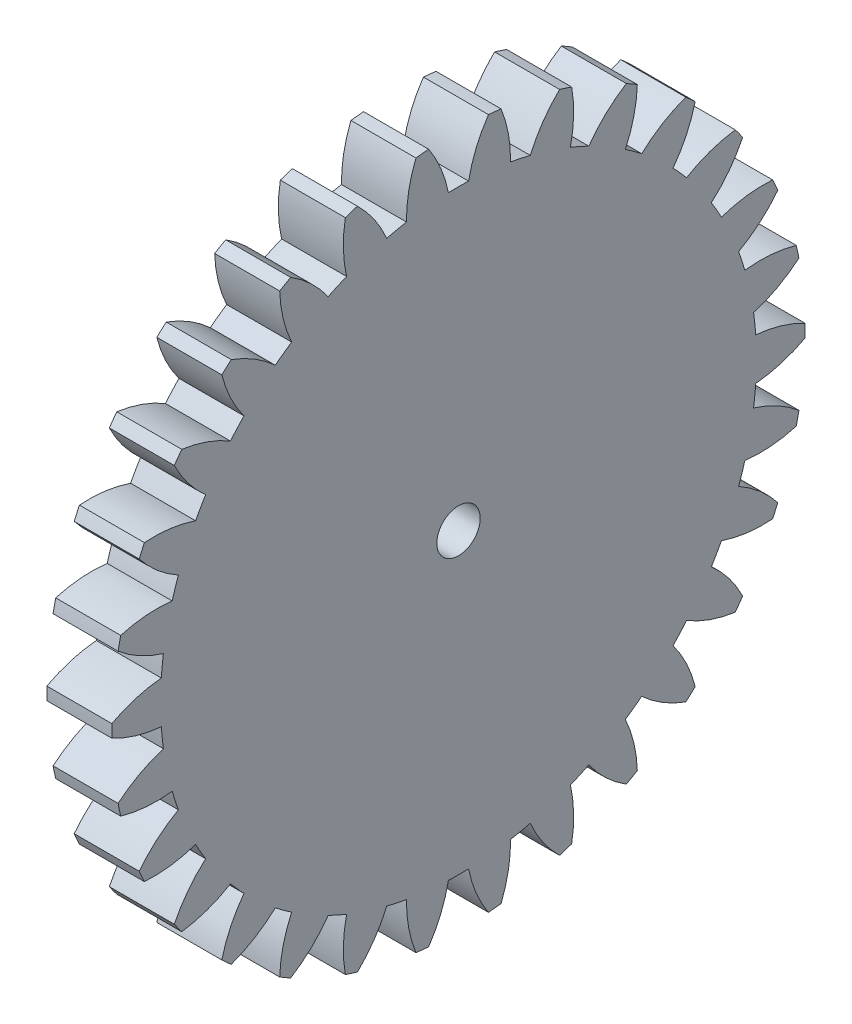
SolidWorks part; units mm, degrees
ref_plane "Plane1" through (0, 0, 0) normal (0, 0, 1) x (1, 0, 0)
ref_plane "Plane2" through (0, 0, 0) normal (0, 1, 0) x (1, 0, 0)
ref_plane "Plane3" through (0, 0, 0) normal (1, 0, 0) x (0, 0, -1)
sketch "HoldingSke" plane through (0, 0, 0) normal (0, 1, 0) x (1, 0, 0)
  line L0 (0, 0) -> (0.866, -0.5)
  line L1 (-15, 0) -> (100, 0) construction
  line L2 (0, 0) -> (-2.1039, 2.3779)
  line L3 (0, 0) -> (-11.863, 4.5341)
  line L4 (0, 0) -> (7.479, 4.318)
  line L5 (0, 0) -> (-46.8476, -17.4728)
  line L6 (0, 0) -> (-2.4869, -1.6779)
  line L7 (-2.1039, 2.3779) -> (8.6586, 51.2059)
  line L8 (-76.2, 54.61) -> (-75.9, 54.61)
  line L9 (-71.009, 38.7566) -> (-53.1078, 45.2721)
  line L10 (-76.2, 71.12) -> (104.1128, 71.12)
  line L11 (0, 0) -> (-3, 0)
  line L12 (-76.2, 101.6) -> (-76.162, 101.6)
  line L13 (24.9733, 27.94) -> (52.9518, 28.4284)
  line L14 (24.9733, 27.94) -> (24.9743, 27.94)
  line L15 (24.9733, 27.94) -> (100.4006, 29.5858)
  line L16 (-63.627, -1) -> (-12.827, -1)
  circle A0 centre (0, 0) radius 1
  circle A1 centre (0, 0) radius 13.749
  circle A2 centre (0, 0) radius 37.5
  circle A3 centre (0, 0) radius 1
  dimension "MHD" = 27.498
  dimension "Hub_dia" = 75
  dimension "Bore" = 2
  dimension "MBD" = 2
  dimension "Num_teeth" = 30
  dimension "Pitch" = 1
  dimension "Overall_len" = 50
  dimension "Show_teeth" = 30
  dimension "Thickness" = 3
  dimension "OAL" = 50.0001
  dimension "T_dim" = 0.3
  dimension "Ap" = 20
  dimension "H" = 19.05
  dimension "Pitch_radius" = 180.3128
  dimension "Width" = 3
  dimension "Backlash" = 0.038
  dimension "Addendum_fac" = 1
  dimension "Dedendum_fac" = 1.25
  dimension "Clearance_fac" = 0.25
  dimension "Dedendum_add" = 0.001
  dimension "Module" = 1
sketch "BasProSke" plane through (0, 0, 0) normal (0, 1, 0) x (1, 0, 0)
  line L0 (-10, 0) -> (60, 0) construction
  line L1 (0, 0) -> (0, 16)
  line L2 (0, 0) -> (3, 0)
  line L3 (3, 0) -> (3, 16)
  line L4 (3, 16) -> (0, 16)
  dimension "Thickness" = 3
  dimension "Diameter" = 32
revolve "Base-Revolve" add sketch "BasProSke" angle 360 about L0
sketch "TooCutSke" plane through (0, 0, 0) normal (1, 0, 0) x (0, 0, -1)
  line L1 (0, 0) -> (0, 107) construction
  line L2 (0, 0) -> (-0.8515, 14.9758) construction
  line L3 (0, 0) -> (-3.1323, 29.8014) construction
  line L4 (-0.8515, 14.9758) -> (-1.5661, 14.9007) construction
  arc A0 (0.4664, 13.7411) -> (-0.4664, 13.7411) centre (0, 0) ccw
  arc A1 (1.3975, 15.9644) -> (-1.3975, 15.9644) centre (0, 0) ccw
  circle A2 centre (0, 0) radius 15 construction
  circle A3 centre (0, 0) radius 14.0954 construction
  arc A4 (-0.4664, 13.7411) -> (-1.3975, 15.9644) centre (-6.3534, 12.5823) ccw
  arc A5 (1.3975, 15.9644) -> (0.4664, 13.7411) centre (6.3534, 12.5823) ccw
  dimension "Root_dia" = 27.498
  dimension "Overcut_dia" = 32.0508
  dimension "Pitch_dia" = 30
  dimension "Base_dia" = 28.1908
  dimension "Flank_rad" = 6
  dimension "Half_ang" = 6
  dimension "Half_CT" = 0.7185
extrude "ToothCut" cut sketch "TooCutSke" along normal through all
fillet "Breaks" [suppressed] radius 0.02
fillet "RootFillets" [suppressed] radius 0.251
pattern_circular "TeethCuts" count 30 every 12 about axis through (-10, 0, 0) along (1, 0, 0) of "ToothCut", "RootFillets", "Breaks"
sketch "HubNeaOneSke" plane through (0, 0, 0) normal (-1, 0, 0) x (0, 0, 1)
  circle A0 centre (0, 0) radius 13.749
  dimension "Diameter" = 27.498
extrude "HubNearOne" [suppressed] add sketch "HubNeaOneSke" along normal blind 47.0001
sketch "HubNeaBotSke" plane through (0, 0, 0) normal (-1, 0, 0) x (0, 0, 1)
  circle A0 centre (0, 0) radius 13.749
  dimension "Diameter" = 27.498
extrude "HubNearBoth" [suppressed] add sketch "HubNeaBotSke" along normal blind 23.5
ref_plane "FarPln" through (3, 0, 0) normal (1, 0, 0) x (0, 0, -1)
sketch "HubFarSke" plane through (3, 0, 0) normal (1, 0, 0) x (0, 0, -1)
  circle A0 centre (0, 0) radius 13.749
  dimension "Diameter" = 27.498
extrude "HubFar" [suppressed] add sketch "HubFarSke" along normal blind 23.5
sketch "BorSke" plane through (0, 0, 0) normal (1, 0, 0) x (0, 0, -1)
  circle A0 centre (0, 0) radius 1
  dimension "Diameter" = 2
extrude "Bore" cut sketch "BorSke" along normal mid plane 100.0001
sketch "KeySke" plane through (0, 0, 0) normal (1, 0, 0) x (0, 0, -1)
  line L0 (-0.4, 0) -> (-0.4, 1.3)
  line L1 (-0.4, 1.3) -> (0.4, 1.3)
  line L2 (0.4, 1.3) -> (0.4, 0)
  line L3 (0, 0) -> (0, 34) construction
  line L4 (-0.4, 0) -> (0.4, 0)
  dimension "Offset" = 1.3
  dimension "Width" = 0.8
extrude "Keyway" [suppressed] cut sketch "KeySke" along normal mid plane 100.0001
pattern_circular "Keyway2" [suppressed] count 2 every 90 about axis through (-10, 0, 0) along (1, 0, 0)
equation "' \"Module@HoldingSke\" = 6.35"
equation "' \"Num_teeth@HoldingSke\" = 12"
equation "' \"Ap@HoldingSke\" =  20"
equation "' \"Ap@HoldingSke\" = 20"
equation "' \"Width@HoldingSke\" = 0.5 * 25.4"
equation "' \"Hub_dia@HoldingSke\"= 1 * 25.4"
equation "' \"Hub_dia@HoldingSke\" = 1 * 25.4"
equation "' \"Overall_len@HoldingSke\" = 1.0 * 25.4"
equation "' \"Bore@HoldingSke\" = 0.75 * 25.4"
equation "' \"T_dim@HoldingSke\" = 0.1 * 25.4"
equation "' \"Width@KeySke\" = 0.25 * 25.4"
equation "' \"Show_teeth@HoldingSke\" = 13"
equation "' \"Backlash@HoldingSke\" = 0.009 * 25.4"
equation "' \"Addendum_fac@HoldingSke\" = 1.0"
equation "' \"Dedendum_fac@HoldingSke\" = 1.25"
equation "' \"Dedendum_add@HoldingSke\" = 0.00005 * 25.4"
equation "' \"Clearance_fac@HoldingSke\" = 0.25"
equation "\"Pitch@HoldingSke\" = 1 / \"Module@HoldingSke\""
equation "\"Overcut_dia@TooCutSke\" = (\"Num_teeth@HoldingSke\" + 2 * \"Addendum_fac@HoldingSke\") / \"Pitch@HoldingSke\" + 0.002 * 25.4"
equation "\"Pitch_dia@TooCutSke\" = \"Num_teeth@HoldingSke\" / \"Pitch@HoldingSke\""
equation "\"Base_dia@TooCutSke\" = \"Num_teeth@HoldingSke\" / \"Pitch@HoldingSke\" * cos((\"Ap@HoldingSke\"  * 3.14159265 / 180))"
equation "\"Root_dia@TooCutSke\" = (\"Num_teeth@HoldingSke\" + 2) / \"Pitch@HoldingSke\" - 2 * (\"Addendum_fac@HoldingSke\" + \"Dedendum_fac@HoldingSke\") / \"Pitch@HoldingSke\" - \"Dedendum_add@HoldingSke\" * 2"
equation "\"Half_ang@TooCutSke\" = 180 / \"Num_teeth@HoldingSke\""
equation "\"Half_CT@TooCutSke\" = \"Num_teeth@HoldingSke\" / \"Pitch@HoldingSke\" * sin((3.14159265 / 2 / \"Num_teeth@HoldingSke\")) / 2 - 7 * \"Backlash@HoldingSke\" / 4"
equation "\"Flank_rad@TooCutSke\" = \"Num_teeth@HoldingSke\" / \"Pitch@HoldingSke\" / 5"
equation "\"Radius@RootFillets\" = \"Clearance_fac@HoldingSke\" / \"Pitch@HoldingSke\" + \"Dedendum_add@HoldingSke\""
equation "\"Break_rad@Breaks\" = 0.02 / \"Pitch@HoldingSke\""
equation "\"Thickness@HoldingSke\" = \"Width@HoldingSke\""
equation "\"OAL@HoldingSke\" = \"Thickness@HoldingSke\""
equation "\"MHD@HoldingSke\" = (\"Num_teeth@HoldingSke\" + 2) / \"Pitch@HoldingSke\" - 2 * (\"Addendum_fac@HoldingSke\" + \"Dedendum_fac@HoldingSke\")  / \"Pitch@HoldingSke\" - \"Dedendum_add@HoldingSke\" * 2"
equation "\"MBD@HoldingSke\" = (\"Num_teeth@HoldingSke\" + 2) / \"Pitch@HoldingSke\" - 2 * (\"Addendum_fac@HoldingSke\" + \"Dedendum_fac@HoldingSke\")  / \"Pitch@HoldingSke\" - \"Dedendum_add@HoldingSke\" * 2 - 0.002 * 25.4"
equation "\"MHD@HoldingSke\" = ((sgn( \"MHD@HoldingSke\" - \"Hub_dia@HoldingSke\" )-1)*( \"MHD@HoldingSke\" - \"Hub_dia@HoldingSke\" ))/-2+ \"Hub_dia@HoldingSke\""
equation "\"MBD@HoldingSke\" = ((sgn( \"MBD@HoldingSke\" - \"Bore@HoldingSke\" )-1)*( \"MBD@HoldingSke\" - \"Bore@HoldingSke\" ))/-2+ \"Bore@HoldingSke\""
equation "\"OAL@HoldingSke\" = ((sgn( \"OAL@HoldingSke\" - \"Overall_len@HoldingSke\" )+1)*( \"OAL@HoldingSke\" - \"Overall_len@HoldingSke\" ))/2 + \"Overall_len@HoldingSke\" + 0.000002 * 25.4"
equation "\"Num_teeth@TeethCuts\" = int( \"Show_teeth@HoldingSke\" ) + 1"
equation "\"Num_teeth@TeethCuts\" = ((sgn( \"Num_teeth@TeethCuts\" - \"Num_teeth@HoldingSke\" )-1)*( \"Num_teeth@TeethCuts\" - \"Num_teeth@HoldingSke\" ))/-2+ \"Num_teeth@HoldingSke\""
equation "\"Num_teeth@TeethCuts\" = ((sgn( \"Num_teeth@TeethCuts\" - 2.0)+1)*( \"Num_teeth@TeethCuts\" - 2.0))/2 +2.0"
equation "\"Angle@TeethCuts\" = 360.0 / \"Num_teeth@HoldingSke\""
equation "\"Diameter@BasProSke\" = (\"Num_teeth@HoldingSke\" + 2 * \"Addendum_fac@HoldingSke\") / \"Pitch@HoldingSke\""
equation "\"Thickness@BasProSke\"  = \"Thickness@HoldingSke\""
equation "' \"Fillet_rad@BasProSke\" =  \"Thickness@HoldingSke\" * 0.05"
equation "' \"Fillet_rad@BasProSke\" = \"Thickness@HoldingSke\" * 0.05"
equation "\"MHD@HoldingSke\" = ((sgn( \"MHD@HoldingSke\" - \"Root_dia@TooCutSke\" )-1)*( \"MHD@HoldingSke\" - \"Root_dia@TooCutSke\" ))/-2+ \"Root_dia@TooCutSke\""
equation "\"Diameter@HubNeaOneSke\" = \"MHD@HoldingSke\""
equation "\"Length@HubNearOne\" = \"OAL@HoldingSke\" - \"Thickness@BasProSke\""
equation "\"Diameter@HubNeaBotSke\" = \"MHD@HoldingSke\""
equation "\"Length@HubNearBoth\" = ( \"OAL@HoldingSke\" - \"Thickness@BasProSke\" ) / 2.0"
equation "\"Thickness@FarPln\" = \"Thickness@BasProSke\""
equation "\"Diameter@HubFarSke\" = \"MHD@HoldingSke\""
equation "\"Length@HubFar\" = ( \"OAL@HoldingSke\" - \"Thickness@BasProSke\" ) / 2.0"
equation "\"Diameter@BorSke\" = \"MBD@HoldingSke\""
equation "\"D1@Bore\" = \"OAL@HoldingSke\" * 2.0"
equation "\"D1@Keyway\" = \"OAL@HoldingSke\" * 2.0"
equation "\"Offset@KeySke\" = \"T_dim@HoldingSke\" + \"MBD@HoldingSke\" / 2.0"
